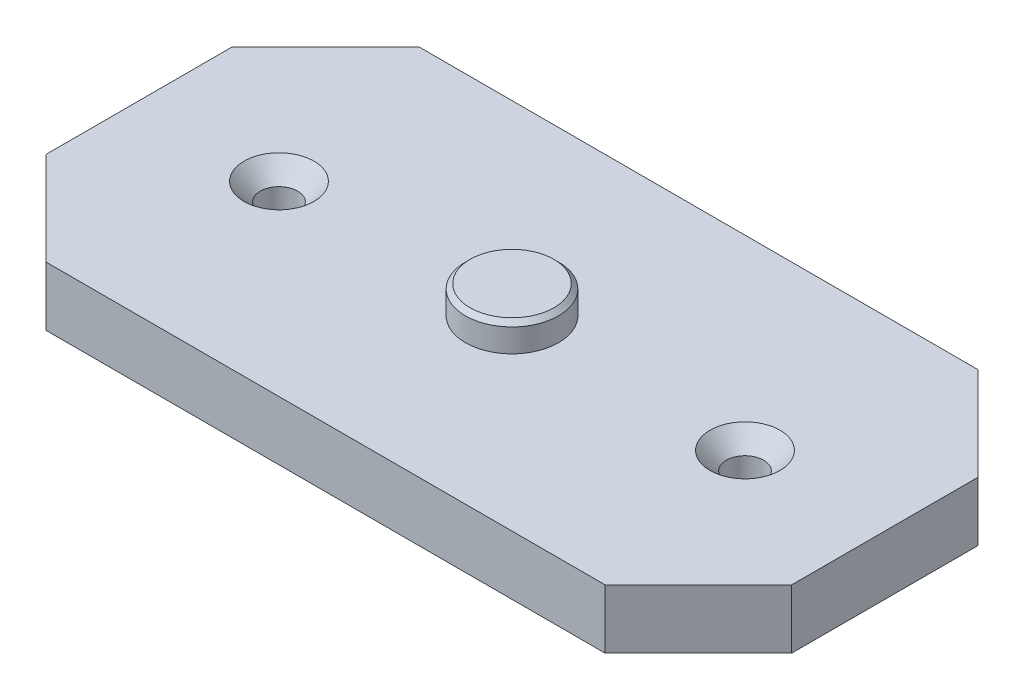
SolidWorks part; units mm, degrees
ref_plane "Front Plane" through (0, 0, 0) normal (0, 0, 1) x (1, 0, 0)
ref_plane "Top Plane" through (0, 0, 0) normal (0, 1, 0) x (1, 0, 0)
ref_plane "Right Plane" through (0, 0, 0) normal (1, 0, 0) x (0, 0, -1)
sketch "Sketch1" plane through (0, 0, 0) normal (0, 1, 0) x (1, 0, 0)
  line L1 (-40, -20) -> (40, -20)
  line L2 (-40, -20) -> (-40, 20)
  line L3 (-40, 20) -> (40, 20)
  line L4 (40, -20) -> (40, 20)
  line L5 (-40, -20) -> (40, 20) construction
  line L6 (-40, 20) -> (40, -20) construction
  point P0 (0, 0)
  dimension "D1" = 80
  dimension "D2" = 40
extrude "Boss-Extrude1" add sketch "Sketch1" along normal blind 6.35
sketch "Sketch7" plane through (0, 6.35, 0) normal (0, 1, 0) x (1, 0, 0)
  line L0 (25, 0) -> (-25, 0) construction
  point P0 (-25, 0)
  point P2 (25, 0)
  dimension "D1" = 50
hole_wizard "CSK for M3 Flat Head Machine Screw1" positions "Sketch7" profile "Sketch6" countersink size "M3" standard "ANSI Metric" end condition up to next
sketch "Sketch6" plane through (-25, 6.35, 0) normal (1, 0, 0) x (0, 0, 1)
  line L0 (0, 0) -> (0, 6.35)
  line L1 (0, 6.35) -> (2, 6.35)
  line L2 (2, 6.35) -> (2, 1.9098)
  line L3 (2, 1.9098) -> (3.75, 0)
  line L5 (3.75, 0) -> (0, 0)
  line L6 (-2, 1.9098) -> (-3.75, 0) construction
  line L11 (0, -6.35) -> (0, 107.95) construction
  dimension "Thru Hole Dia." = 4
  dimension "Thru Hole Depth" = 6.35
  dimension "Near C'Sink Dia." = 7.5
  dimension "Near C'Sink Angle" = 85
sketch "Sketch8" plane through (0, 6.35, 0) normal (0, 1, 0) x (1, 0, 0)
  circle A0 centre (0, 0) radius 5
  dimension "D1" = 10
extrude "Boss-Extrude2" add sketch "Sketch8" along normal blind 3 and the other way blind 15
chamfer "Chamfer1" distance 10 angle 45 4 edges at (-40, 3.175, 20) (-40, 3.175, -20) (40, 3.175, -20) (40, 3.175, 20)
chamfer "Chamfer2" distance 0.5 angle 45 2 edges at (0, -8.65, 5) (0, 9.35, 5)
